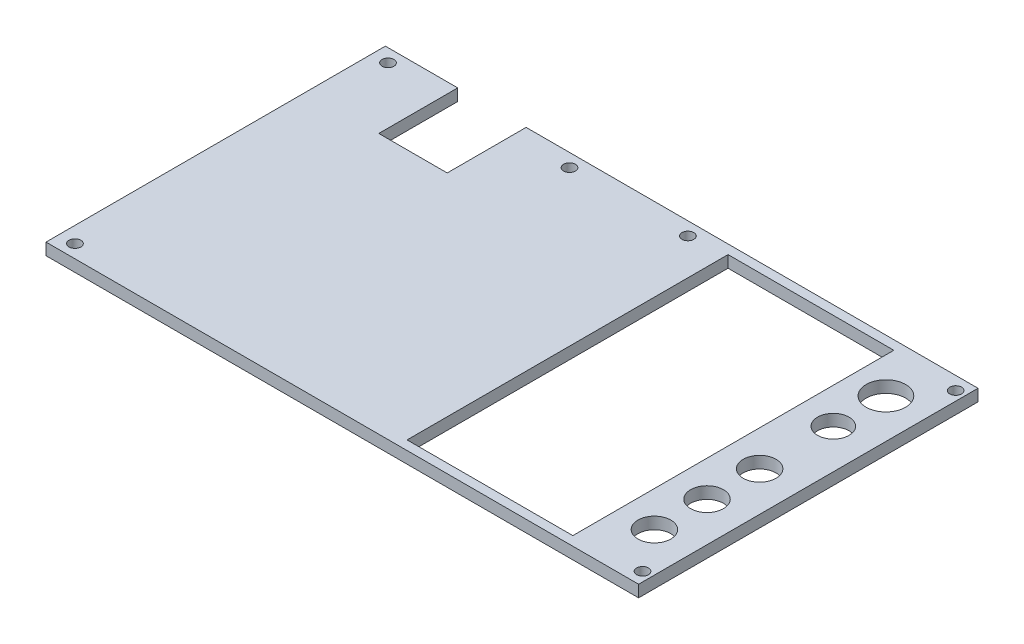
SolidWorks part; units mm, degrees
ref_plane "Front Plane" through (0, 0, 0) normal (0, 0, 1) x (1, 0, 0)
ref_plane "Top Plane" through (0, 0, 0) normal (0, 1, 0) x (1, 0, 0)
ref_plane "Right Plane" through (0, 0, 0) normal (1, 0, 0) x (0, 0, -1)
sketch "Sketch1" plane through (0, 0, 0) normal (0, 1, 0) x (1, 0, 0)
  line L0 (0, 64.5) -> (0, -64.5) construction
  line L1 (-112.62, -64.5) -> (112.62, -64.5)
  line L2 (-112.62, -64.5) -> (-112.62, 64.5)
  line L3 (-112.62, 64.5) -> (112.62, 64.5)
  line L4 (112.62, -64.5) -> (112.62, 64.5)
  dimension "D1" = 225.24
  dimension "D2" = 129
extrude "Boss-Extrude1" add sketch "Sketch1" along normal mid plane 4.5
sketch "Sketch2" plane through (0, 2.25, 0) normal (0, 1, 0) x (1, 0, 0)
  line L0 (112.62, -64.5) -> (112.62, 64.5) construction
  line L1 (21.12, -61) -> (84.12, -61)
  line L2 (21.12, -61) -> (21.12, 61)
  line L3 (21.12, 61) -> (84.12, 61)
  line L4 (84.12, -61) -> (84.12, 61)
  line L5 (112.62, 0) -> (84.12, 0) construction
  line L9 (21.62, -60.5) -> (21.62, 60.5) construction
  line L10 (83.62, -60.5) -> (21.62, -60.5) construction
  line L11 (83.62, 60.5) -> (83.62, -60.5) construction
  dimension "D1" = 0.5
  dimension "D2" = 0.5
  dimension "D3" = 0.5
extrude "Cut-Extrude1" cut sketch "Sketch2" against normal through all
sketch "Sketch3" plane through (0, 2.25, 0) normal (0, 1, 0) x (1, 0, 0)
  line L0 (-112.62, -64.5) -> (112.62, -64.5) construction
  line L1 (112.62, 64.5) -> (-112.62, 64.5) construction
  line L2 (112.62, -64.5) -> (112.62, 64.5) construction
  circle A0 centre (97.62, -43.5) radius 6.25
  circle A1 centre (97.62, -23.5) radius 6.25
  circle A2 centre (97.62, -3.5) radius 6.25
  circle A3 centre (97.62, 24.5) radius 6
  circle A4 centre (97.62, 44.5) radius 7.5
  dimension "D1" = 12.5
  dimension "D6" = 15
  dimension "D7" = 12
  dimension "D2" = 20
  dimension "D3" = 20
  dimension "D4" = 15
  dimension "D5" = 21
  dimension "D8" = 20
  dimension "D9" = 20
extrude "Cut-Extrude2" cut sketch "Sketch3" against normal through all
sketch "Sketch4" plane through (0, 2.25, 0) normal (0, 1, 0) x (1, 0, 0)
  line L0 (112.62, 64.5) -> (-112.62, 64.5) construction
  line L1 (-85.13, 64.5) -> (-59.13, 64.5)
  line L2 (-85.13, 64.5) -> (-85.13, 34.5)
  line L3 (-85.13, 34.5) -> (-59.13, 34.5)
  line L4 (-59.13, 64.5) -> (-59.13, 34.5)
  line L5 (-112.62, 64.5) -> (-112.62, -64.5) construction
  dimension "D1" = 26
  dimension "D2" = 27.49
  dimension "D3" = 30
extrude "Cut-Extrude3" cut sketch "Sketch4" against normal through all
hole_wizard "M4 Clearance Hole1" positions "Sketch5" profile "Sketch6" hole size "M4" standard "ANSI Metric"
sketch "Sketch5" plane through (0, 2.25, 0) normal (0, 1, 0) x (1, 0, 0)
  point P0 (-106.62, -59.5)
  point P2 (-106.62, 59.5)
  point P4 (-37.64, 59.5)
  point P6 (7.36, 59.5)
  point P8 (109.12, 59.5)
  point P10 (109.12, -59.5)
sketch "Sketch6" plane through (-106.62, 2.25, 59.5) normal (1, 0, 0) x (0, 0, 1)
  line L0 (0, 0) -> (0, 13.3519)
  line L1 (0, 13.3519) -> (2.25, 12)
  line L2 (2.25, 12) -> (2.25, 0)
  line L5 (2.25, 0) -> (0, 0)
  line L10 (0, 13.3519) -> (-2.25, 12) construction
  line L11 (0, -6.35) -> (0, 107.95) construction
  dimension "Hole Dia." = 4.5
  dimension "Hole Depth" = 12
  dimension "Drill Angle" = 118
